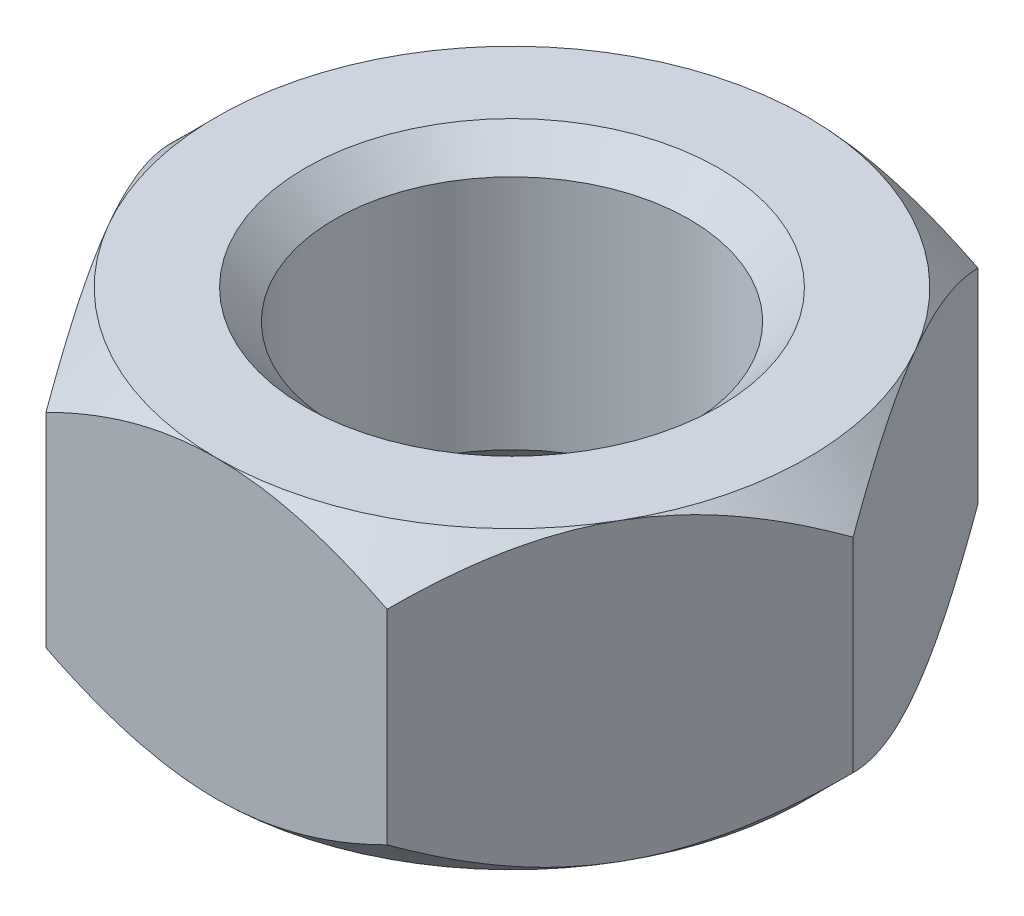
SolidWorks part; units mm, degrees
material "Cast Stainless Steel"
ref_plane "Front Plane" through (0, 0, 0) normal (0, 0, 1) x (1, 0, 0)
ref_plane "Top Plane" through (0, 0, 0) normal (0, 1, 0) x (1, 0, 0)
ref_plane "Right Plane" through (0, 0, 0) normal (1, 0, 0) x (0, 0, -1)
sketch "Sketch1" plane through (0, 0, 0) normal (0, 1, 0) x (1, 0, 0)
  line L0 (-5.7735, 0) -> (5.7735, 0) construction
  line L1 (5.7735, 0) -> (2.8868, 5)
  line L2 (2.8868, 5) -> (-2.8868, 5)
  line L3 (-2.8868, 5) -> (-5.7735, 0)
  line L4 (-5.7735, 0) -> (-2.8868, -5)
  line L5 (-2.8868, -5) -> (2.8868, -5)
  line L6 (2.8868, -5) -> (5.7735, 0)
  circle A0 centre (0, 0) radius 5 construction
  circle A1 centre (0, 0) radius 3
  point P12 (0, 0)
  dimension "D1" = 6
  dimension "D2" = 10
extrude "Boss-Extrude1" add sketch "Sketch1" along normal blind 5
sketch "Sketch3" plane through (0, 0, 0) normal (1, 0, 0) x (0, 0, -1)
  line L0 (-5, 0) -> (-6.5, 1.5)
  line L1 (-6.5, 1.5) -> (-6.5, 0)
  line L2 (-6.5, 0) -> (-5, 0)
  line L4 (-5, 2.5) -> (5, 2.5) construction
  line L6 (5, 5) -> (5, 0) construction
  line L7 (-6.5, 5) -> (-5, 5)
  line L8 (-6.5, 3.5) -> (-6.5, 5)
  line L9 (-5, 5) -> (-6.5, 3.5)
  line L10 (0, 0) -> (0, 5) construction
  line L12 (-5, 5) -> (-5, 0) construction
  point P7 (0, 2.5)
  dimension "D1" = 2.5
  dimension "D2" = 45
  dimension "D3" = 1.5
revolve "Cut-Revolve1" cut sketch "Sketch3" angle 360 about L10
chamfer "Chamfer1" distance 0.5 angle 45 2 edges at (0, 0, 3) (0, 5, 3)
equation "\"d\"= 6"
equation "\"m\"= 5"
equation "\"s\"= 10"
equation "\"e\"= 11.05"
equation "\"D1@Sketch1\"=\"d\""
equation "\"D2@Sketch1\"=\"s\""
equation "\"D1@Boss-Extrude1\"=\"m\""
equation "\"D1@Sketch3\"=\"m\"/2"
equation "\"D3@Sketch3\"=\"D1@Sketch3\"-1"
equation "\"D1@Chamfer1\"=\"s\"/20"
